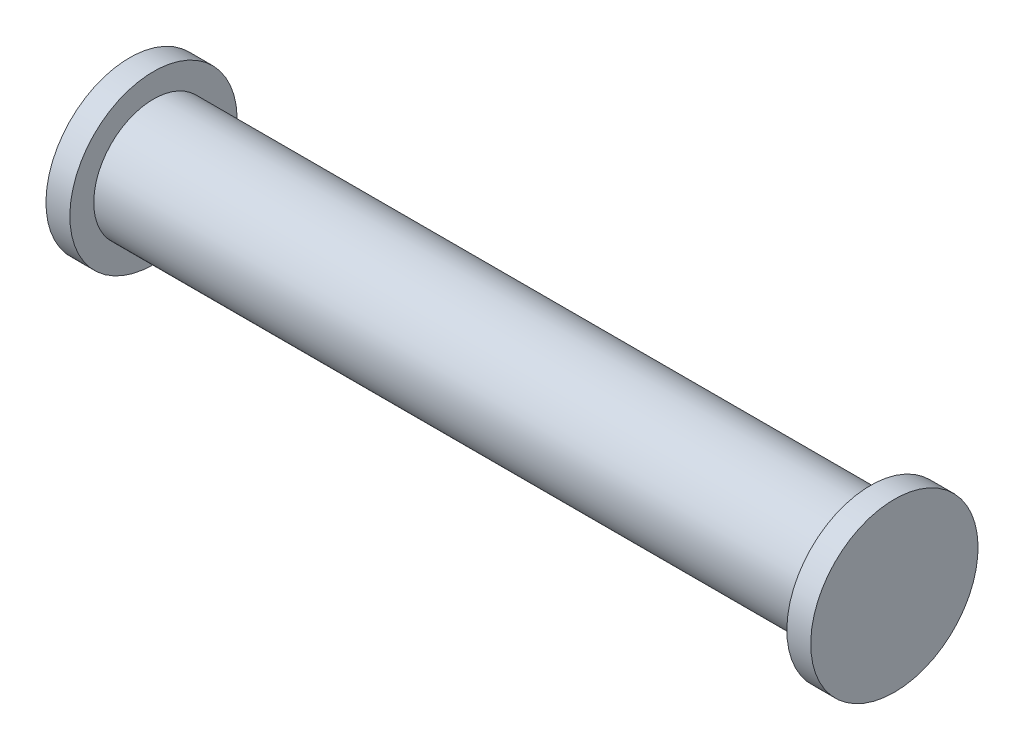
SolidWorks part; units mm, degrees
material "6061 Alloy"
ref_plane "Front Plane" through (0, 0, 0) normal (0, 0, 1) x (1, 0, 0)
ref_plane "Top Plane" through (0, 0, 0) normal (0, 1, 0) x (1, 0, 0)
ref_plane "Right Plane" through (0, 0, 0) normal (1, 0, 0) x (0, 0, -1)
sketch "Sketch1" plane through (0, 0, 0) normal (0, 0, 1) x (1, 0, 0)
  line L0 (0, 0) -> (0, 5) construction
  line L1 (-30, 5) -> (30, 5)
  line L2 (-30, 5) -> (-30, 7)
  line L3 (-30, 7) -> (-32, 7)
  line L4 (-32, 7) -> (-32, 0)
  line L5 (-32, 0) -> (32, 0)
  line L6 (32, 0) -> (32, 7)
  line L7 (32, 7) -> (30, 7)
  line L8 (30, 7) -> (30, 5)
  point P5 (0, 5)
  dimension "D1" = 5
  dimension "D2" = 60
  dimension "D3" = 2
  dimension "D4" = 2
  dimension "D5" = 7
  dimension "D6" = 2
revolve "Revolve1" add sketch "Sketch1" angle 360 about L5
